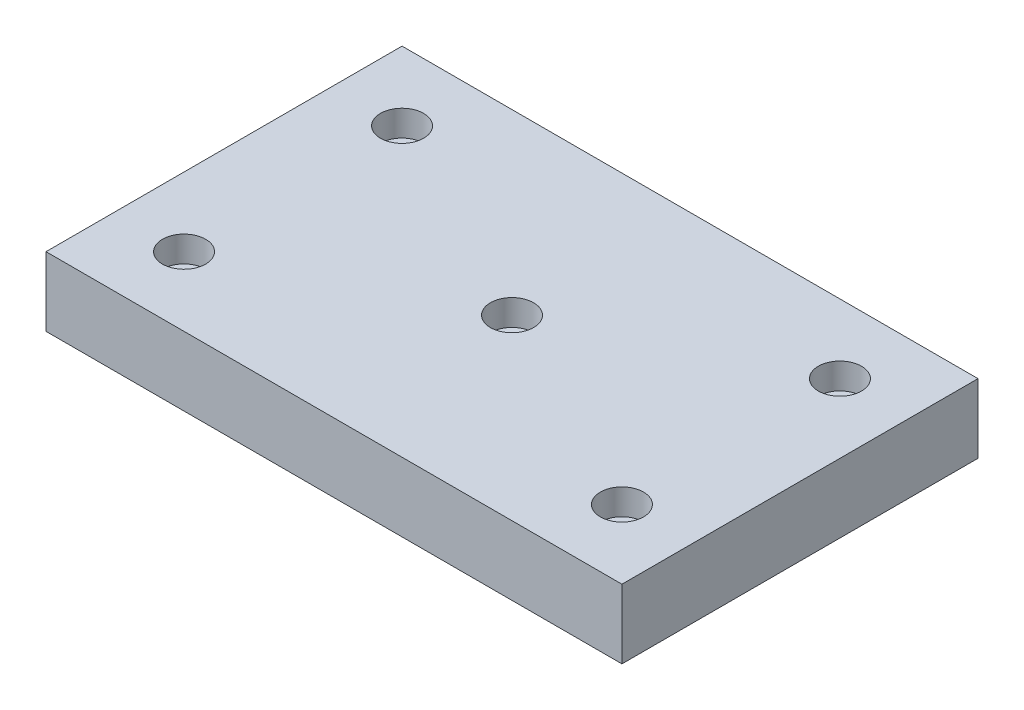
SolidWorks part; units mm, degrees
ref_plane "Front Plane" through (0, 0, 0) normal (0, 0, 1) x (1, 0, 0)
ref_plane "Top Plane" through (0, 0, 0) normal (0, 1, 0) x (1, 0, 0)
ref_plane "Right Plane" through (0, 0, 0) normal (1, 0, 0) x (0, 0, -1)
sketch "Sketch1" plane through (0, 0, 0) normal (0, 1, 0) x (1, 0, 0)
  line L1 (-105.9663, -65.5095) -> (105.9663, -65.5095)
  line L2 (-105.9663, -65.5095) -> (-105.9663, 65.5095)
  line L3 (-105.9663, 65.5095) -> (105.9663, 65.5095)
  line L4 (105.9663, -65.5095) -> (105.9663, 65.5095)
  line L5 (-105.9663, -65.5095) -> (105.9663, 65.5095) construction
  line L6 (-105.9663, 65.5095) -> (105.9663, -65.5095) construction
  point P0 (0, 0)
extrude "Boss-Extrude1" add sketch "Sketch1" along normal blind 25.4
hole_wizard "CBORE for 3/8 Socket Head Cap Screw1" positions "Sketch3" profile "Sketch4" counterbore size "3/8" standard "ANSI Inch" end condition up to next
sketch "Sketch3" plane through (0, 25.4, 0) normal (0, 1, 0) x (1, 0, 0)
  line L1 (-80.5663, -40.1095) -> (80.5663, -40.1095) construction
  line L2 (-80.5663, -40.1095) -> (-80.5663, 40.1095) construction
  line L3 (-80.5663, 40.1095) -> (80.5663, 40.1095) construction
  line L4 (80.5663, -40.1095) -> (80.5663, 40.1095) construction
  line L5 (-80.5663, -40.1095) -> (80.5663, 40.1095) construction
  line L6 (-80.5663, 40.1095) -> (80.5663, -40.1095) construction
  line L7 (105.9663, 65.5095) -> (-105.9663, 65.5095) construction
  line L8 (-105.9663, 65.5095) -> (-105.9663, -65.5095) construction
  point P0 (-80.5663, -40.1095)
  point P2 (-80.5663, 40.1095)
  point P4 (80.5663, 40.1095)
  point P6 (80.5663, -40.1095)
  point P10 (0, 0)
  dimension "D1" = 25.4
  dimension "D2" = 25.4
sketch "Sketch4" plane through (-80.5663, 25.4, 40.1095) normal (1, 0, 0) x (0, 0, 1)
  line L0 (0, 0) -> (0, 25.4)
  line L1 (0, 25.4) -> (5.0419, 25.4)
  line L3 (5.0419, 25.4) -> (5.0419, 9.525)
  line L4 (5.0419, 9.525) -> (7.9375, 9.525)
  line L5 (7.9375, 9.525) -> (7.9375, 0)
  line L7 (7.9375, 0) -> (0, 0)
  line L11 (0, -6.35) -> (0, 107.95) construction
  dimension "Thru Hole Dia." = 10.0838
  dimension "Thru Hole Depth" = 25.4
  dimension "C'Bore Dia." = 15.875
  dimension "C'Bore Depth" = 9.525
